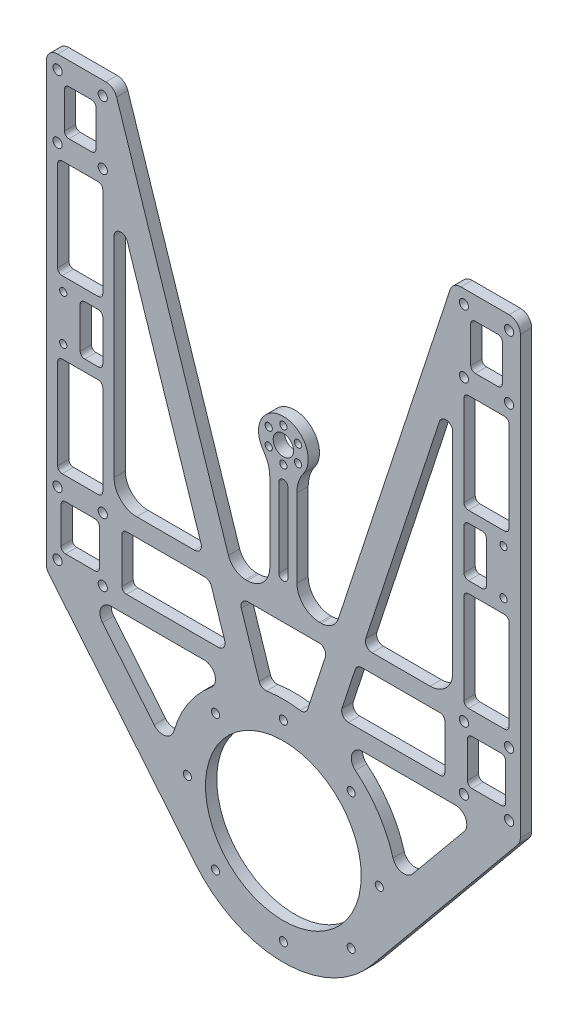
SolidWorks part; units mm, degrees
material "Thornel Mat VMA"
ref_plane "前视基准面" through (0, 0, 0) normal (0, 0, 1) x (1, 0, 0)
ref_plane "上视基准面" through (0, 0, 0) normal (0, 1, 0) x (1, 0, 0)
ref_plane "右视基准面" through (0, 0, 0) normal (1, 0, 0) x (0, 0, -1)
other "Configuration Table"
sketch "草图2" plane through (0, 0, 0) normal (0, 0, 1) x (1, 0, 0)
  line L0 (-90, 180) -> (-90, -20) construction
  line L1 (-105, -20) -> (105, -20)
  line L2 (-105, -20) -> (-105, 20)
  line L3 (-105, 20) -> (105, 20)
  line L4 (105, -20) -> (105, 20)
  line L5 (-105, -20) -> (105, 20) construction
  line L6 (-105, 20) -> (105, -20) construction
  line L7 (-105, -20) -> (-75, -20)
  line L8 (-105, -20) -> (-105, 180)
  line L9 (-105, 180) -> (-75, 180)
  line L10 (-75, -20) -> (-75, 180)
  line L11 (105, -20) -> (75, -20)
  line L12 (105, -20) -> (105, 180)
  line L13 (105, 180) -> (75, 180)
  line L14 (75, -20) -> (75, 180)
  line L15 (-90, 80) -> (-97.5, 80) construction
  line L16 (-97.5, 90) -> (-97.5, 70) construction
  line L17 (0, 20) -> (0, -49980) construction
  circle A0 centre (-97.5, 90) radius 1.6
  circle A1 centre (-97.5, 70) radius 1.6
  circle A2 centre (97.5, 70) radius 1.6
  circle A3 centre (97.5, 90) radius 1.6
  point P0 (0, 0)
  point P19 (-97.5, 80)
  point P23 (0, 20)
  dimension "D7" = 3.2
  dimension "D1" = 210
  dimension "D2" = 30
  dimension "D3" = 40
  dimension "D4" = 200
  dimension "D5" = 20
  dimension "D6" = 7.5
extrude "凸台-拉伸1" add sketch "草图2" along normal blind 5 contours L3 L10 L9 L8 A1 A0 | L1 L10 L3 L2 | L1 L14 L3 L10 | L14 L1 L4 L3 | L14 L3 L12 L13 A2 A3
fillet "圆角4" radius 10 2 edges at (75, 20, 2.5) (-75, 20, 2.5)
sketch "草图10" plane through (0, 0, 5) normal (0, 0, 1) x (1, 0, 0)
  line L0 (0, 0) -> (0, -50000) construction
  line L1 (-65, 20) -> (65, 20) construction
  line L2 (-6, 20) -> (6, 20)
  line L3 (-6, 20) -> (-6, 83)
  line L4 (-6, 83) -> (6, 83)
  line L5 (6, 20) -> (6, 83)
  line L6 (0, 91) -> (0, 80) construction
  circle A0 centre (0, 80) radius 11
  circle A1 centre (0, 87.5) radius 1.6
  circle A2 centre (6.4952, 83.75) radius 1.6
  circle A3 centre (6.4952, 76.25) radius 1.6
  circle A4 centre (0, 72.5) radius 1.6
  circle A5 centre (-6.4952, 76.25) radius 1.6
  circle A6 centre (-6.4952, 83.75) radius 1.6
  circle A7 centre (0, 80) radius 4.5
  point P27 (0, 80)
  line M26 (65, 20) -> (-65, 20)
  dimension "D1" = 6
  dimension "D3" = 22
  dimension "D5" = 3.5
  dimension "D6" = 3.2
  dimension "D8" = 9
  dimension "D2" = 3
  dimension "D4" = 60
  dimension "D7" = 6
extrude "凸台-拉伸5" add sketch "草图10" against normal up to surface (5 mm away) contours A0 L3 L2 L5 | A5 L3 A0 L5 A3 L4 A4 | A5 L3 L4 L5 A3 A0 A6 A2 A1 | A0 L3 L5 M26
fillet "圆角6" radius 15 2 edges at (-6, 70.7805, 2.5) (6, 70.7805, 2.5)
fillet "圆角7" radius 10 2 edges at (-6, 20, 2.5) (6, 20, 2.5)
sketch "草图11" plane through (0, 0, 5) normal (0, 0, 1) x (1, 0, 0)
  line L0 (-6, 64.6703) -> (-6, 30) construction
  line L1 (-6, 47.3351) -> (6, 47.3351) construction
  line L2 (6, 30) -> (6, 64.6703) construction
  line L3 (0, 64.8351) -> (0, 29.8351) construction
  line L4 (2, 64.8351) -> (2, 29.8351)
  line L5 (-2, 64.8351) -> (-2, 29.8351)
  arc A0 (2, 64.8351) -> (-2, 64.8351) centre (0, 64.8351) ccw
  arc A1 (-2, 29.8351) -> (2, 29.8351) centre (0, 29.8351) ccw
  point P10 (0, 47.3351)
  dimension "D1" = 4
  dimension "D2" = 35
extrude "切除-拉伸4" cut sketch "草图11" against normal blind 25
sketch "草图18" plane through (0, 0, 0) normal (0, 0, -1) x (-1, 0, 0)
  circle A0 centre (0, 80) radius 4.5
extrude "切除-拉伸8" cut sketch "草图18" against normal blind 10
sketch "草图19" plane through (0, 0, 5) normal (0, 0, 1) x (1, 0, 0)
  line L0 (0, 80) -> (0, -68) construction
  line L1 (-105, -20) -> (-38.9705, -100.1178)
  line L2 (105, -20) -> (38.9705, -100.1178)
  line L3 (-15.6924, -20) -> (15.6924, -20)
  line L4 (-105, -20) -> (105, -20) construction
  line L5 (-105, -20) -> (105, -20)
  circle A0 centre (0, -68) radius 42.5 construction
  circle A1 centre (0, 80) radius 4.5 construction
  circle A2 centre (0, -25.5) radius 1.8
  circle A3 centre (30.052, -37.948) radius 1.8
  circle A4 centre (42.5, -68) radius 1.8
  circle A5 centre (30.052, -98.052) radius 1.8
  circle A6 centre (0, -110.5) radius 1.8
  circle A7 centre (-30.052, -98.052) radius 1.8
  circle A8 centre (-42.5, -68) radius 1.8
  circle A9 centre (-30.052, -37.948) radius 1.8
  arc A10 (-15.6924, -20) -> (15.6924, -20) centre (0, -68) ccw
  circle A11 centre (0, -68) radius 34.5
  point P25 (0, -68)
  line M10 (-105, -20) -> (105, -20)
  dimension "D1" = 148
  dimension "D2" = 85
  dimension "D3" = 3.6
  dimension "D5" = 8
  dimension "D6" = 8
  dimension "D4" = 8
extrude "凸台-拉伸6" add sketch "草图19" against normal up to surface (5 mm away) contours A10 L1 M10 | A10 A11 A2 A3 A4 A5 A6 A7 A8 A9 M10 | A10 L2 M10 up to face at (0, 47.3351, 0)
sketch "草图20" plane through (0, 0, 5) normal (0, 0, 1) x (1, 0, 0)
  line L0 (105, 180) -> (75, 180) construction
  line L1 (80, -14) -> (100, -14) construction
  line L2 (80, -14) -> (80, 14) construction
  line L3 (80, 14) -> (100, 14) construction
  line L4 (100, -14) -> (100, 14) construction
  line L5 (80, -14) -> (100, 14) construction
  line L6 (80, 14) -> (100, -14) construction
  line L7 (80, 146) -> (100, 146) construction
  line L8 (80, 146) -> (80, 174) construction
  line L9 (80, 174) -> (100, 174) construction
  line L10 (100, 146) -> (100, 174) construction
  line L11 (80, 146) -> (100, 174) construction
  line L12 (80, 174) -> (100, 146) construction
  line L13 (0, 0) -> (0, -50000) construction
  line L14 (-80, 174) -> (-100, 146) construction
  line L15 (-80, 146) -> (-100, 174) construction
  line L16 (-100, 146) -> (-100, 174) construction
  line L17 (-80, 174) -> (-100, 174) construction
  line L18 (-80, 146) -> (-80, 174) construction
  line L19 (-80, 146) -> (-100, 146) construction
  line L20 (-80, 14) -> (-100, -14) construction
  line L21 (-80, -14) -> (-100, 14) construction
  line L22 (-100, -14) -> (-100, 14) construction
  line L23 (-80, 14) -> (-100, 14) construction
  line L24 (-80, -14) -> (-80, 14) construction
  line L25 (-80, -14) -> (-100, -14) construction
  circle A0 centre (100, -14) radius 2.05
  circle A1 centre (80, 14) radius 2.05
  circle A2 centre (100, 14) radius 2.05
  circle A3 centre (80, -14) radius 2.05
  circle A4 centre (80, 174) radius 2.05
  circle A5 centre (100, 174) radius 2.05
  circle A6 centre (100, 146) radius 2.05
  circle A7 centre (80, 146) radius 2.05
  circle A8 centre (-80, 146) radius 2.05
  circle A9 centre (-100, 146) radius 2.05
  circle A10 centre (-100, 174) radius 2.05
  circle A11 centre (-80, 174) radius 2.05
  circle A12 centre (-80, -14) radius 2.05
  circle A13 centre (-100, 14) radius 2.05
  circle A14 centre (-80, 14) radius 2.05
  circle A15 centre (-100, -14) radius 2.05
  point P0 (90, 0)
  point P10 (90, 160)
  point P41 (-90, 160)
  point P42 (-90, 0)
  dimension "D1" = 5
  dimension "D2" = 6
  dimension "D3" = 4.1
  dimension "D6" = 6
  dimension "D4" = 20
  dimension "D5" = 28
extrude "切除-拉伸9" cut sketch "草图20" against normal blind 10
sketch "草图22" plane through (0, 0, 5) normal (0, 0, 1) x (1, 0, 0)
  line L0 (-90, 96) -> (-90, 91) construction
  line L1 (-100, 146) -> (-80, 146) construction
  line L2 (-100, 146) -> (-100, 174) construction
  line L3 (-100, 174) -> (-80, 174) construction
  line L4 (-80, 146) -> (-80, 174) construction
  line L5 (-100, 146) -> (-80, 174) construction
  line L6 (-100, 174) -> (-80, 146) construction
  line L7 (-100, -14) -> (-80, -14) construction
  line L8 (-100, -14) -> (-100, 14) construction
  line L9 (-100, 14) -> (-80, 14) construction
  line L10 (-80, -14) -> (-80, 14) construction
  line L11 (-100, -14) -> (-80, 14) construction
  line L12 (-100, 14) -> (-80, -14) construction
  line L13 (-100, 20) -> (-80, 20)
  line L14 (-100, 20) -> (-100, 64)
  line L15 (-100, 64) -> (-80, 64)
  line L16 (-80, 20) -> (-80, 64)
  line L17 (-100, 20) -> (-80, 64) construction
  line L18 (-100, 64) -> (-80, 20) construction
  line L19 (-90, 69) -> (-80, 69)
  line L20 (-90, 69) -> (-90, 91)
  line L21 (-90, 91) -> (-80, 91)
  line L22 (-80, 69) -> (-80, 91)
  line L23 (-90, 69) -> (-80, 91) construction
  line L24 (-90, 91) -> (-80, 69) construction
  line L25 (-100, 96) -> (-80, 96)
  line L26 (-100, 96) -> (-100, 140)
  line L27 (-100, 140) -> (-80, 140)
  line L28 (-80, 96) -> (-80, 140)
  line L29 (-100, 96) -> (-80, 140) construction
  line L30 (-100, 140) -> (-80, 96) construction
  line L31 (-97, 150) -> (-83, 150)
  line L32 (-97, 150) -> (-97, 170)
  line L33 (-97, 170) -> (-83, 170)
  line L34 (-83, 150) -> (-83, 170)
  line L35 (-97, 150) -> (-83, 170) construction
  line L36 (-97, 170) -> (-83, 150) construction
  line L37 (-98.5, -10) -> (-81.5, -10)
  line L38 (-98.5, -10) -> (-98.5, 10)
  line L39 (-98.5, 10) -> (-81.5, 10)
  line L40 (-81.5, -10) -> (-81.5, 10)
  line L41 (-98.5, -10) -> (-81.5, 10) construction
  line L42 (-98.5, 10) -> (-81.5, -10) construction
  line L43 (0, 0) -> (0, -50000) construction
  line L44 (98.5, 10) -> (81.5, -10) construction
  line L45 (98.5, -10) -> (81.5, 10) construction
  line L46 (97, 170) -> (83, 150) construction
  line L47 (97, 150) -> (83, 170) construction
  line L48 (100, 140) -> (80, 96) construction
  line L49 (100, 96) -> (80, 140) construction
  line L50 (90, 91) -> (80, 69) construction
  line L51 (90, 69) -> (80, 91) construction
  line L52 (100, 64) -> (80, 20) construction
  line L53 (100, 20) -> (80, 64) construction
  line L54 (100, 14) -> (80, -14) construction
  line L55 (100, -14) -> (80, 14) construction
  line L56 (80, -14) -> (80, 14) construction
  line L57 (100, 14) -> (80, 14) construction
  line L58 (100, -14) -> (100, 14) construction
  line L59 (100, -14) -> (80, -14) construction
  line L60 (100, 174) -> (80, 146) construction
  line L61 (100, 146) -> (80, 174) construction
  line L62 (80, 146) -> (80, 174) construction
  line L63 (100, 174) -> (80, 174) construction
  line L64 (100, 146) -> (100, 174) construction
  line L65 (100, 146) -> (80, 146) construction
  line L66 (90, 96) -> (90, 91) construction
  line L67 (81.5, -10) -> (81.5, 10)
  line L68 (98.5, 10) -> (81.5, 10)
  line L69 (98.5, -10) -> (98.5, 10)
  line L70 (98.5, -10) -> (81.5, -10)
  line L71 (83, 150) -> (83, 170)
  line L72 (97, 170) -> (83, 170)
  line L73 (97, 150) -> (97, 170)
  line L74 (97, 150) -> (83, 150)
  line L75 (80, 96) -> (80, 140)
  line L76 (100, 140) -> (80, 140)
  line L77 (100, 96) -> (100, 140)
  line L78 (100, 96) -> (80, 96)
  line L79 (80, 69) -> (80, 91)
  line L80 (90, 91) -> (80, 91)
  line L81 (90, 69) -> (90, 91)
  line L82 (90, 69) -> (80, 69)
  line L83 (80, 20) -> (80, 64)
  line L84 (100, 64) -> (80, 64)
  line L85 (100, 20) -> (100, 64)
  line L86 (100, 20) -> (80, 20)
  circle A0 centre (-97.5, 90) radius 1.6 construction
  circle A1 centre (-97.5, 70) radius 1.6 construction
  point P0 (-90, 160)
  point P5 (-90, 0)
  point P10 (-90, 42)
  point P15 (-85, 80)
  point P20 (-90, 118)
  point P25 (-90, 0)
  point P29 (-90, 160)
  point P76 (90, 160)
  point P77 (90, 0)
  point P78 (90, 118)
  point P79 (85, 80)
  point P80 (90, 42)
  dimension "D7" = 6
  dimension "D1" = 3
  dimension "D2" = 4
  dimension "D3" = 4
  dimension "D4" = 3
  dimension "D5" = 6
  dimension "D6" = 6
  dimension "D8" = 5
  dimension "D9" = 5
extrude "切除-拉伸10" cut sketch "草图22" against normal blind 10
fillet "圆角8" radius 2 40 edges at (-100, 20, 2.5) (-100, 64, 2.5) (-80, 64, 2.5) (-80, 20, 2.5) (80, 20, 2.5) (80, 64, 2.5) (100, 64, 2.5) (100, 20, 2.5) (81.5, -10, 2.5) (81.5, 10, 2.5) (98.5, 10, 2.5) (98.5, -10, 2.5) (83, 150, 2.5) (83, 170, 2.5) (97, 170, 2.5) (80, 96, 2.5) (80, 140, 2.5) (100, 140, 2.5) (100, 96, 2.5) (80, 69, 2.5) (80, 91, 2.5) (90, 91, 2.5) (90, 69, 2.5) (-90, 69, 2.5) (-90, 91, 2.5) (-80, 91, 2.5) (-80, 69, 2.5) (-100, 96, 2.5) (-100, 140, 2.5) (-80, 140, 2.5) (-80, 96, 2.5) (-98.5, -10, 2.5) (-98.5, 10, 2.5) (-81.5, 10, 2.5) (-81.5, -10, 2.5) (-97, 150, 2.5) (-97, 170, 2.5) (-83, 170, 2.5) (-83, 150, 2.5) (97, 150, 2.5)
sketch "草图23" plane through (0, 0, 5) normal (0, 0, 1) x (1, 0, 0)
  line L0 (105, -20) -> (105, 180) construction
  line L1 (-105, -20) -> (105, -20) construction
  line L2 (-105, -20) -> (-105, 20) construction
  line L3 (-105, 20) -> (105, 20) construction
  line L4 (105, -20) -> (105, 20) construction
  line L5 (16, 20) -> (65, 20) construction
  line L6 (-86.8581, -20) -> (-50.3629, -64.2818)
  line L7 (-86.8581, -20) -> (-15.6924, -20)
  line L8 (-105, -20) -> (-38.9705, -100.1178) construction
  line L9 (15.6924, -20) -> (86.8581, -20)
  line L10 (86.8581, -20) -> (47.2986, -68)
  line L11 (105, -20) -> (38.9705, -100.1178) construction
  circle A0 centre (0, -68) radius 50.5
  arc A1 (-38.9705, -100.1178) -> (38.9705, -100.1178) centre (0, -68) ccw construction
  point P25 (17.8077, -17.9956)
  point P26 (15.2181, -19.8476)
  point P27 (15.7795, -20)
  dimension "D1" = 14
  dimension "D2" = 14
extrude "切除-拉伸11" cut sketch "草图23" against normal blind 10 contours A0 L7 L6 | A0 L10 L9
fillet "圆角9" radius 5 6 edges at (-50.3629, -64.2818, 2.5) (-86.8581, -20, 2.5) (-15.6924, -20, 2.5) (15.6924, -20, 2.5) (86.8581, -20, 2.5) (50.3629, -64.2818, 2.5)
sketch "草图24" plane through (0, 0, 5) normal (0, 0, 1) x (1, 0, 0)
  line L3 (-81.5, -8) -> (-81.5, 8) construction
  line L4 (71.5, -12) -> (-71.5, -12)
  line L5 (71.5, -12) -> (71.5, 12)
  line L6 (71.5, 12) -> (-71.5, 12)
  line L7 (-71.5, -12) -> (-71.5, 12)
  line L8 (71.5, -12) -> (-71.5, 12) construction
  line L9 (71.5, 12) -> (-71.5, -12) construction
  line L10 (-65, 20) -> (-16, 20) construction
  line L11 (6, 30) -> (6, 64.6703) construction
  line L12 (-6, -12) -> (6, -12)
  line L13 (-6, -12) -> (-6, 12)
  line L14 (-6, 12) -> (6, 12)
  line L15 (6, -12) -> (6, 12)
  line L16 (-6, -12) -> (6, 12) construction
  line L17 (-6, 12) -> (6, -12) construction
  point P0 (0, 0)
  point P10 (0, 0)
  dimension "D1" = 10
  dimension "D2" = 8
extrude "切除-拉伸12" cut sketch "草图24" against normal blind 10 contours L4 L13 L6 L7 | L15 L4 L5 L6
fillet "圆角10" radius 2 8 edges at (-71.5, -12, 2.5) (-71.5, 12, 2.5) (-6, -12, 2.5) (6, 12, 2.5) (71.5, 12, 2.5) (71.5, -12, 2.5) (6, -12, 2.5) (-6, 12, 2.5)
sketch "草图25" plane through (0, 0, 5) normal (0, 0, 1) x (1, 0, 0)
  line L0 (-75, 160.7421) -> (0, -68) construction
  line L1 (-75, 30) -> (-75, 180) construction
  line L2 (0, -68) -> (75, 160.7421) construction
  line L3 (75, 30) -> (75, 180) construction
  line L4 (-75, 160.7421) -> (75, 160.7421) construction
  line L5 (-75, 180) -> (-12.047, -12)
  line L6 (-8, -12) -> (-69.5, -12) construction
  line L7 (75, 180) -> (12.047, -12)
  line L8 (69.5, -12) -> (8, -12) construction
  line L9 (-75, 141.4842) -> (-24.6756, -12)
  line L10 (75, 141.4842) -> (24.6756, -12)
  line L11 (-75, 180) -> (-75, 141.4842)
  line L12 (75, 180) -> (75, 141.4842)
  line L13 (-24.6756, -12) -> (-12.047, -12)
  line L14 (12.047, -12) -> (24.6756, -12)
  line L15 (6, -10) -> (6, 10) construction
  line L16 (69.5, 12) -> (8, 12) construction
  line L17 (-6, -10) -> (-6, 10) construction
  line L18 (-8, 12) -> (-69.5, 12) construction
  line L19 (24.6756, -12) -> (8, -12)
  line L20 (6, -10) -> (6, 10)
  line L21 (32.5447, 12) -> (8, 12)
  line L22 (-8, -12) -> (-24.6756, -12)
  line L23 (-6, -10) -> (-6, 10)
  line L24 (-8, 12) -> (-32.5447, 12)
  arc A0 (6, -10) -> (8, -12) centre (8, -10) ccw construction
  arc A1 (8, 12) -> (6, 10) centre (8, 10) ccw construction
  arc A2 (-8, -12) -> (-6, -10) centre (-8, -10) ccw construction
  arc A3 (-6, 10) -> (-8, 12) centre (-8, 10) ccw construction
  arc A4 (6, -10) -> (8, -12) centre (8, -10) ccw
  arc A5 (8, 12) -> (6, 10) centre (8, 10) ccw
  arc A6 (-8, -12) -> (-6, -10) centre (-8, -10) ccw
  arc A7 (-6, 10) -> (-8, 12) centre (-8, 10) ccw
  dimension "D1" = 12
  dimension "D2" = 6
  dimension "D3" = 12
extrude "凸台-拉伸7" add sketch "草图25" against normal up to surface (5 mm away) contours L24 L5 L11 L9 | L5 L24 L9 L13 | L23 A7 L24 L5 L22 A6 | L21 A5 L20 A4 L19 L7 | L10 L21 L7 L14 | L21 L10 L12 L7 up to face at (38.75, 0, 0)
fillet "圆角11" radius 3 8 edges at (-75, 141.4842, 2.5) (-35.1677, 20, 2.5) (-24.6756, -12, 2.5) (-32.5447, 12, 2.5) (75, 141.4842, 2.5) (24.6756, -12, 2.5) (32.5447, 12, 2.5) (35.1677, 20, 2.5)
sketch "草图26" plane through (0, 0, 5) normal (0, 0, 1) x (1, 0, 0)
  line L0 (-22.5392, 20) -> (-9.921, -18.4841) construction
  line L2 (9.921, -18.4841) -> (22.5392, 20) construction
  line L3 (75, 180) -> (22.5392, 20) construction
  line L4 (-75, 180) -> (-22.5392, 20) construction
  line L6 (-19.9161, 12) -> (19.9161, 12)
  line L9 (0, -20) -> (0, -19.2945) construction
  line L10 (0, 0) -> (0, 12) construction
  line L11 (-34.7182, 12) -> (-69.5, 12) construction
  line L12 (-19.9161, 12) -> (-9.921, -18.4841)
  line L13 (19.9161, 12) -> (9.921, -18.4841)
  line L15 (0, -17.5) -> (0, 0) construction
  arc A0 (9.921, -18.4841) -> (-9.921, -18.4841) centre (0, -68) ccw
  arc A1 (48.5618, -54.1435) -> (31.928, -28.8739) centre (0, -68) ccw construction
extrude "切除-拉伸13" cut sketch "草图26" against normal blind 10 contours L13 A0 L12 L6
fillet "圆角13" radius 3 4 edges at (19.9161, 12, 2.5) (9.921, -18.4841, 2.5) (-19.9161, 12, 2.5) (-9.921, -18.4841, 2.5)
fillet "圆角14" radius 8 2 edges at (-22.5392, 20, 2.5) (22.5392, 20, 2.5)
fillet "圆角15" radius 5 6 edges at (75, 180, 2.5) (105, 180, 2.5) (105, -20, 2.5) (-105, 180, 2.5) (-75, 180, 2.5) (-105, -20, 2.5)
